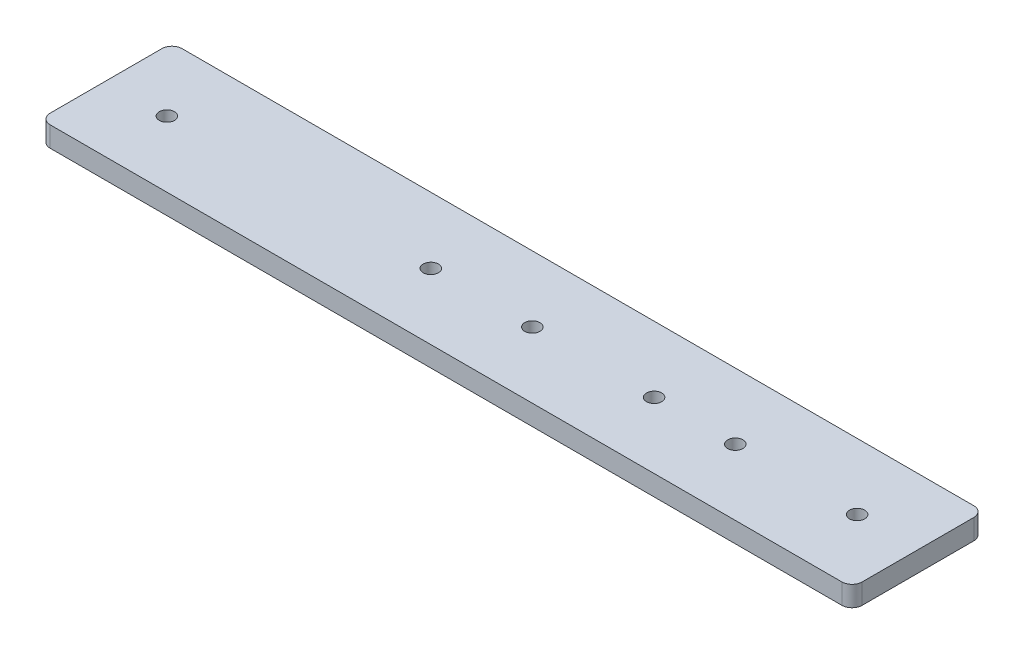
SolidWorks part; units mm, degrees
ref_plane "Front Plane" through (0, 0, 0) normal (0, 0, 1) x (1, 0, 0)
ref_plane "Top Plane" through (0, 0, 0) normal (0, 1, 0) x (1, 0, 0)
ref_plane "Right Plane" through (0, 0, 0) normal (1, 0, 0) x (0, 0, -1)
sketch "Sketch1" plane through (0, 0, 0) normal (0, 1, 0) x (1, 0, 0)
  line L0 (-200, 0) -> (200, 0) construction
  line L1 (200, -32.5) -> (-200, -32.5)
  line L2 (200, -32.5) -> (200, 32.5)
  line L3 (200, 32.5) -> (-200, 32.5)
  line L4 (-200, -32.5) -> (-200, 32.5)
  line L5 (200, -32.5) -> (-200, 32.5) construction
  line L6 (200, 32.5) -> (-200, -32.5) construction
  circle A0 centre (-170, 0) radius 3.75
  circle A1 centre (-40, 0) radius 3.75
  circle A2 centre (10, 0) radius 3.75
  circle A3 centre (70, 0) radius 3.75
  circle A4 centre (110, 0) radius 3.75
  circle A5 centre (170, 0) radius 3.75
  point P0 (0, 0)
  point P20 (110, 0.4551)
  point P21 (110, 0)
  dimension "D3" = 7.5
  dimension "D4" = 130
  dimension "D6" = 180
  dimension "D7" = 240
  dimension "D8" = 340
  dimension "D9" = 280
  dimension "D1" = 400
  dimension "D2" = 65
  dimension "D5" = 30
extrude "Boss-Extrude1" add sketch "Sketch1" along normal blind 10
fillet "Fillet1" radius 5 4 edges at (-200, 5, -32.5) (200, 5, -32.5) (200, 5, 32.5) (-200, 5, 32.5)
